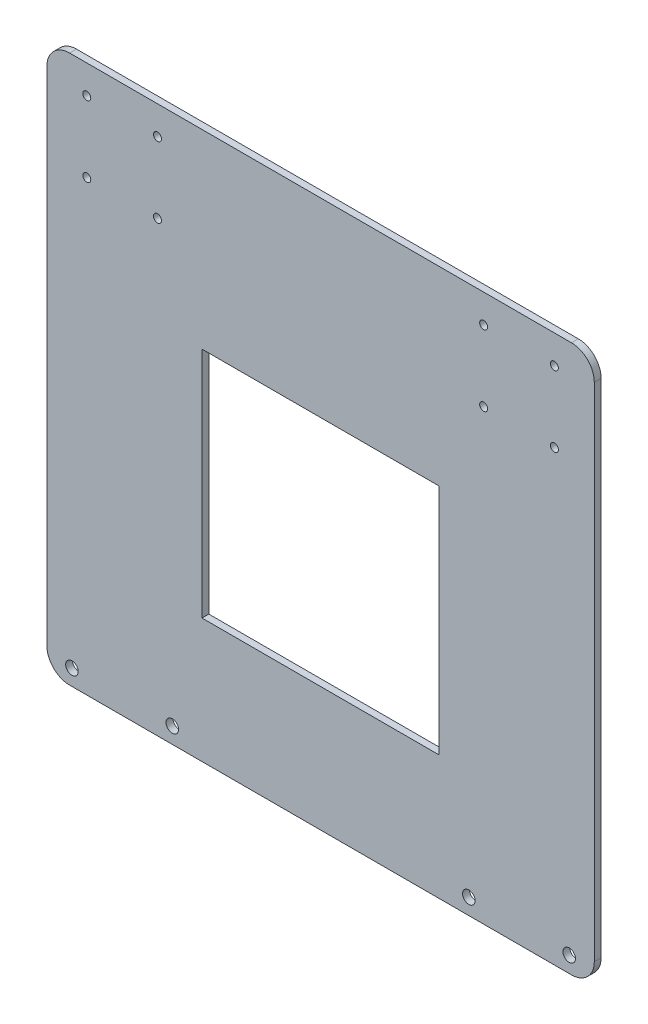
SolidWorks part; units mm, degrees
ref_plane "Front Plane" through (0, 0, 0) normal (0, 0, 1) x (1, 0, 0)
ref_plane "Top Plane" through (0, 0, 0) normal (0, 1, 0) x (1, 0, 0)
ref_plane "Right Plane" through (0, 0, 0) normal (1, 0, 0) x (0, 0, -1)
sketch "Sketch3" plane through (0, 0, 0) normal (0, 0, 1) x (1, 0, 0)
  line L0 (118.969, -110.5155) -> (118.969, 109.4845)
  line L1 (108.969, 119.4845) -> (-111.031, 119.4845)
  line L2 (-121.031, 109.4845) -> (-121.031, -110.5155)
  line L3 (-111.031, -120.5155) -> (108.969, -120.5155)
  arc A0 (118.969, 109.4845) -> (108.969, 119.4845) centre (108.969, 109.4845) ccw
  arc A1 (-111.031, 119.4845) -> (-121.031, 109.4845) centre (-111.031, 109.4845) ccw
  arc A2 (-121.031, -110.5155) -> (-111.031, -120.5155) centre (-111.031, -110.5155) ccw
  arc A3 (108.969, -120.5155) -> (118.969, -110.5155) centre (108.969, -110.5155) ccw
  circle A4 centre (-103.531, 75.9845) radius 1.75
  circle A5 centre (-103.531, 106.9845) radius 1.75
  circle A6 centre (-72.531, 106.9845) radius 1.75
  circle A7 centre (-72.531, 75.9845) radius 1.75
  circle A8 centre (-110.031, -113.5155) radius 2.75
  circle A9 centre (-66.031, -113.5155) radius 2.75
  circle A10 centre (63.969, -113.5155) radius 2.75
  circle A11 centre (101.469, 75.9845) radius 1.75
  circle A12 centre (101.469, 106.9845) radius 1.75
  circle A13 centre (70.469, 106.9845) radius 1.75
  circle A14 centre (70.469, 75.9845) radius 1.75
  circle A15 centre (107.969, -113.5155) radius 2.75
  dimension "D1" = 3.5
  dimension "D2" = 5.5
  dimension "D3" = 10
  dimension "D4" = 63.969
  dimension "D5" = 70.469
  dimension "D6" = 101.469
  dimension "D7" = 107.969
  dimension "D8" = 118.969
  dimension "D9" = 66.031
  dimension "D10" = 72.531
  dimension "D11" = 103.531
  dimension "D12" = 110.031
  dimension "D13" = 121.031
  dimension "D14" = 75.9845
  dimension "D15" = 106.9845
  dimension "D16" = 119.4845
  dimension "D17" = 113.5155
extrude "Boss-Extrude1" add sketch "Sketch3" along normal blind 3
sketch "Sketch4" plane through (0, 0, 3) normal (0, 0, 1) x (1, 0, 0)
  line L0 (-1.031, -120.5155) -> (-1.031, 119.4845) construction
  line L1 (-111.031, -120.5155) -> (108.969, -120.5155) construction
  line L2 (108.969, 119.4845) -> (-111.031, 119.4845) construction
  line L3 (118.969, -110.5155) -> (118.969, 109.4845) construction
  line L4 (-53.031, -66.0155) -> (50.969, -66.0155)
  line L5 (-53.031, -66.0155) -> (-53.031, 36.0845)
  line L6 (-53.031, 36.0845) -> (50.969, 36.0845)
  line L7 (50.969, -66.0155) -> (50.969, 36.0845)
  line L8 (-53.031, -66.0155) -> (50.969, 36.0845) construction
  line L9 (-53.031, 36.0845) -> (50.969, -66.0155) construction
  point P6 (-1.031, -14.9655)
  dimension "D1" = 83.4
  dimension "D2" = 54.5
  dimension "D3" = 68
extrude "Cut-Extrude1" cut sketch "Sketch4" against normal blind 3
